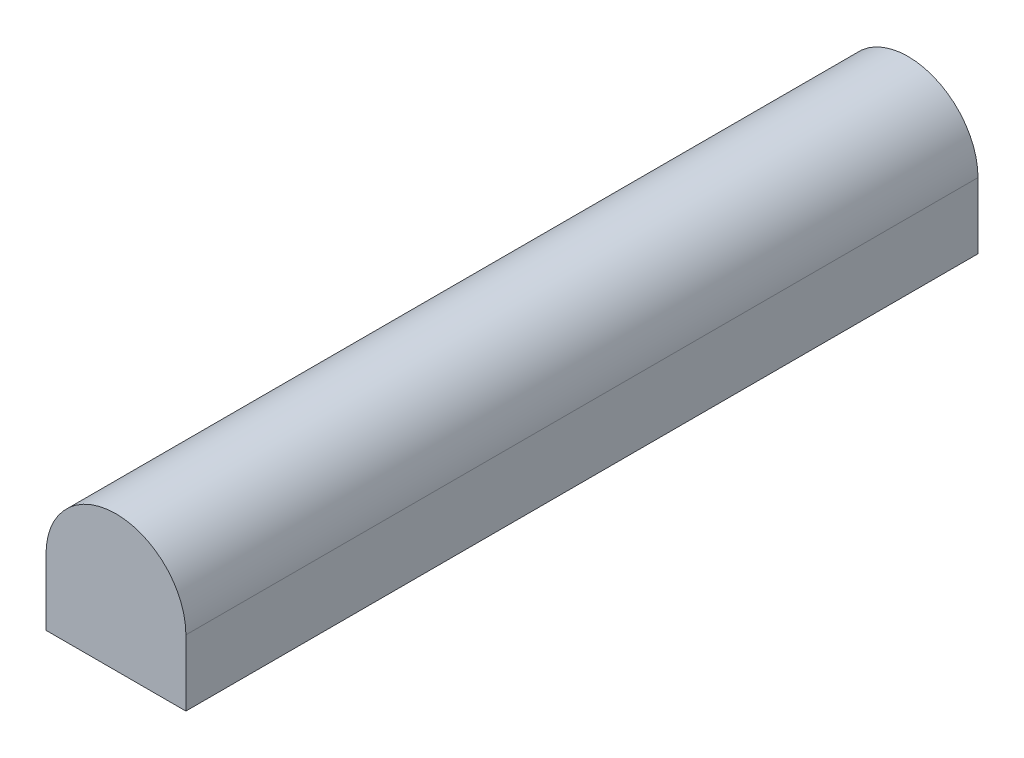
SolidWorks part; units mm, degrees
material "Glass"
ref_plane "Front Plane" through (0, 0, 0) normal (0, 0, 1) x (1, 0, 0)
ref_plane "Top Plane" through (0, 0, 0) normal (0, 1, 0) x (1, 0, 0)
ref_plane "Right Plane" through (0, 0, 0) normal (1, 0, 0) x (0, 0, -1)
sketch "Sketch1" plane through (0, 0, 0) normal (0, 0, 1) x (1, 0, 0)
  line L0 (-1614.9701, 0) -> (-1614.9701, -1524)
  line L1 (1614.9701, 0) -> (1614.9701, -1524)
  arc A0 (-1614.9701, 0) -> (1614.9701, 0) centre (0, 0) cw
  dimension "D1" = 3229.9402
extrude "Extrude-Thin1" add sketch "Sketch1" against normal blind 18288 thin thin type one direction wall 0.0025
sketch "Sketch2" plane through (0, 0, 0) normal (0, 0, 1) x (1, 0, 0)
  line L0 (-1614.9676, 0) -> (-1614.9676, -1524)
  line L1 (1614.9701, 0) -> (1614.9701, -1524)
  line L2 (1614.9701, 0) -> (1614.9701, -1524) construction
  line L3 (1614.9701, -1524) -> (-1614.9676, -1524)
  arc A0 (-1614.9676, 0) -> (1614.9701, 0) centre (0.0013, 0) cw
extrude "Boss-Extrude5" add sketch "Sketch2" against normal blind 0.0025
sketch "Sketch3" plane through (0, 0, -18288) normal (0, 0, -1) x (-1, 0, 0)
  line L0 (-1614.9676, 0) -> (-1614.9676, -1524)
  line L1 (-1614.9676, -1524) -> (1614.9676, -1524)
  line L2 (1614.9676, -1524) -> (1614.9676, 0)
  arc A0 (-1614.9676, 0) -> (1614.9676, 0) centre (0, 0) cw
extrude "Boss-Extrude6" add sketch "Sketch3" along normal blind 0.0025 separate body
